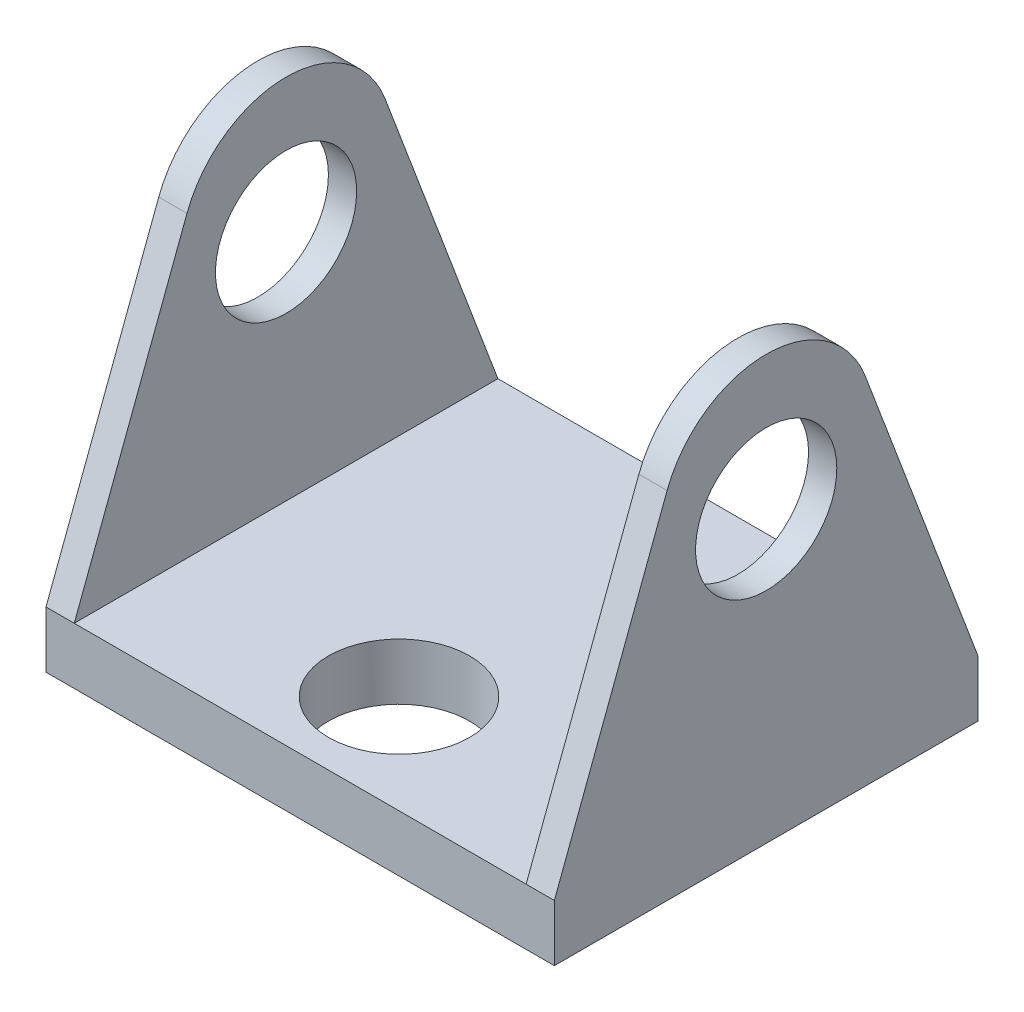
SolidWorks part; units mm, degrees
ref_plane "Front Plane" through (0, 0, 0) normal (0, 0, 1) x (1, 0, 0)
ref_plane "Top Plane" through (0, 0, 0) normal (0, 1, 0) x (1, 0, 0)
ref_plane "Right Plane" through (0, 0, 0) normal (1, 0, 0) x (0, 0, -1)
sketch "Sketch1" plane through (0, 0, 0) normal (0, 0, 1) x (1, 0, 0)
  line L0 (0, 0) -> (0, 16.6364) construction
  line L1 (-16, -2) -> (16, -2)
  line L2 (-16, -2) -> (-16, 2)
  line L3 (-16, 2) -> (16, 2)
  line L4 (16, -2) -> (16, 2)
  line L5 (-16, -2) -> (16, 2) construction
  line L6 (-16, 2) -> (16, -2) construction
  line L7 (-16, -2) -> (-18, -2)
  line L8 (16, -2) -> (18, -2)
  line L9 (16, -2) -> (16, 28)
  line L10 (16, 28) -> (18, 28)
  line L11 (18, -2) -> (18, 28)
  line L12 (-18, -2) -> (-18, 28)
  line L13 (-16, -2) -> (-16, 28)
  line L14 (-16, 28) -> (-18, 28)
  point P0 (0, 0)
  dimension "D1" = 4
  dimension "D2" = 32
  dimension "D3" = 2
  dimension "D4" = 30
extrude "Boss-Extrude1" add sketch "Sketch1" against normal blind 30 contours L13 L14 L12 L7 L2 | L1 L4 L3 L2 | L8 L11 L10 L9 L4
sketch "Sketch2" plane through (0, 0, 0) normal (1, 0, 0) x (0, 0, -1)
  line L0 (30, 28) -> (0, 28) construction
  line L1 (0, -2) -> (0, 28) construction
  line L2 (7.9833, 23.1487) -> (0, 2)
  line L3 (22.0167, 23.1487) -> (30, 2)
  line L4 (30, -2) -> (30, 28) construction
  line L5 (0, 2) -> (-5, 2)
  line L6 (-5, 2) -> (-5, 38)
  line L7 (-5, 38) -> (35, 38)
  line L8 (35, 38) -> (35, 2)
  line L9 (35, 2) -> (30, 2)
  arc A1 (22.0167, 23.1487) -> (7.9833, 23.1487) centre (15, 20.5) ccw
  circle A2 centre (15, 18.5) radius 5
  point P2 (0, 0)
  point P20 (15, 19.5)
  point P21 (15, 28)
  dimension "D1" = 10
  dimension "D2" = 15
  dimension "D4" = 5
  dimension "D3" = 15
  dimension "D5" = 5
  dimension "D6" = 10
  dimension "D7" = 16.5
extrude "Cut-Extrude1" cut sketch "Sketch2" against normal through all both and the other way through all contours A1 L3 L9 L8 L7 L6 L5 L2 | A2
sketch "Sketch3" plane through (0, 0, 0) normal (0, 1, 0) x (1, 0, 0)
  line L0 (0, 0) -> (0, 7) construction
  circle A0 centre (0, 7) radius 5
  dimension "D1" = 10
  dimension "D2" = 7
extrude "Cut-Extrude2" cut sketch "Sketch3" against normal through all both and the other way through all
